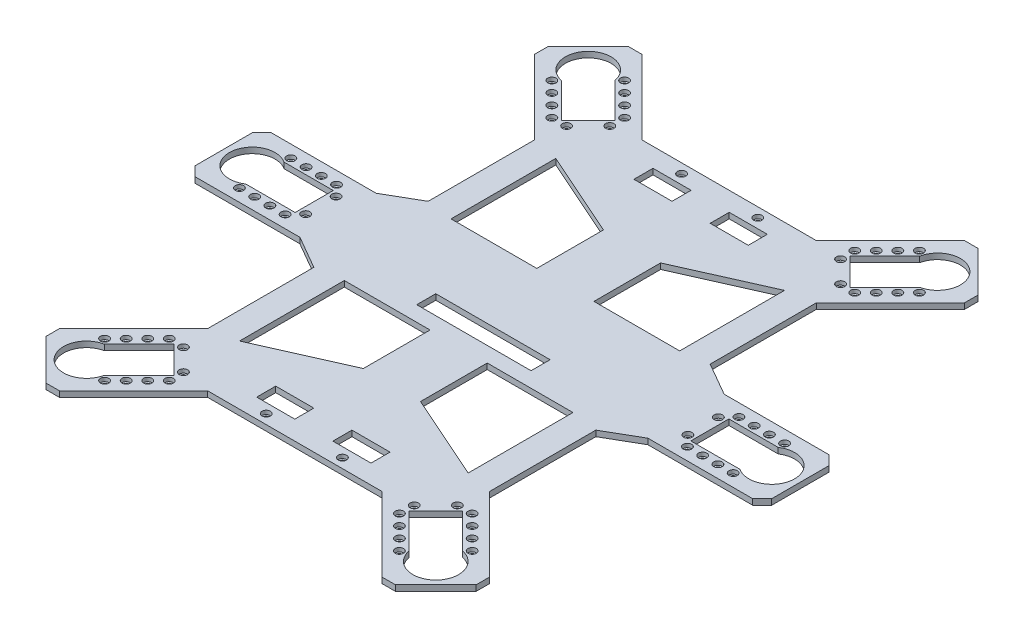
SolidWorks part; units mm, degrees
ref_plane "Front" through (0, 0, 0) normal (0, 0, 1) x (1, 0, 0)
ref_plane "Top" through (0, 0, 0) normal (0, 1, 0) x (1, 0, 0)
ref_plane "Right" through (0, 0, 0) normal (1, 0, 0) x (0, 0, -1)
sketch "草图1" plane through (0, 0, 0) normal (0, 1, 0) x (1, 0, 0)
  line L0 (-45.7157, 114) -> (45.7157, 114)
  line L1 (-74, 0) -> (74, 0) construction
  line L2 (74, -30) -> (91.3205, -20)
  line L3 (91.3205, -20) -> (146.3205, -20)
  line L4 (151.3205, -15) -> (151.3205, 15)
  line L5 (-60, 100) -> (60, -100) construction
  line L6 (-60, -100) -> (60, 100) construction
  line L7 (74, -30) -> (74, -85.7157)
  line L8 (-45.7157, -114) -> (45.7157, -114)
  line L9 (-74, 85.7157) -> (-74, 30)
  line L10 (146.3205, 20) -> (91.3205, 20)
  line L11 (74, 30) -> (91.3205, 20)
  line L12 (0, 100) -> (0, -100) construction
  line L13 (-74, 30) -> (-91.3205, 20)
  line L14 (-146.3205, 20) -> (-91.3205, 20)
  line L15 (-151.3205, -15) -> (-151.3205, 15)
  line L16 (-91.3205, -20) -> (-146.3205, -20)
  line L17 (-74, -30) -> (-91.3205, -20)
  line L18 (-74, -30) -> (-74, -85.7157)
  line L19 (74, 85.7157) -> (74, 30)
  line L20 (91.6777, 152.8909) -> (112.8909, 131.6777)
  line L21 (74, 85.7157) -> (112.8909, 124.6066)
  line L22 (45.7157, 114) -> (84.6066, 152.8909)
  line L23 (-74, 85.7157) -> (-112.8909, 124.6066)
  line L24 (-91.6777, 152.8909) -> (-112.8909, 131.6777)
  line L25 (-45.7157, 114) -> (-84.6066, 152.8909)
  line L26 (74, -85.7157) -> (112.8909, -124.6066)
  line L27 (91.6777, -152.8909) -> (112.8909, -131.6777)
  line L28 (45.7157, -114) -> (84.6066, -152.8909)
  line L29 (-74, -85.7157) -> (-112.8909, -124.6066)
  line L30 (-91.6777, -152.8909) -> (-112.8909, -131.6777)
  line L31 (-45.7157, -114) -> (-84.6066, -152.8909)
  line L32 (-84.6066, 152.8909) -> (-91.6777, 152.8909)
  line L33 (-112.8909, 131.6777) -> (-112.8909, 124.6066)
  line L34 (-151.3205, 15) -> (-146.3205, 20)
  line L35 (-146.3205, -20) -> (-151.3205, -15)
  line L36 (-112.8909, -124.6066) -> (-112.8909, -131.6777)
  line L37 (-84.6066, -152.8909) -> (-91.6777, -152.8909)
  line L38 (84.6066, -152.8909) -> (91.6777, -152.8909)
  line L39 (112.8909, -131.6777) -> (112.8909, -124.6066)
  line L40 (146.3205, -20) -> (151.3205, -15)
  line L41 (151.3205, 15) -> (146.3205, 20)
  line L42 (112.8909, 124.6066) -> (112.8909, 131.6777)
  line L43 (84.6066, 152.8909) -> (91.6777, 152.8909)
  point P0 (0, 0)
  point P12 (74, 30)
  point P16 (74, -30)
extrude "凸台-拉伸1" add sketch "草图1" along normal blind 3
sketch "草图2" plane through (0, 3, 0) normal (0, 1, 0) x (1, 0, 0)
  line L0 (151.3205, 0) -> (87.3942, 0) construction
  line L1 (151.3205, -15) -> (151.3205, 15) construction
  line L2 (103.8205, -10) -> (103.8205, 10)
  line L3 (103.8205, 10) -> (129.6873, 10)
  line L4 (103.8205, -10) -> (129.6873, -10)
  arc A0 (129.6873, -10) -> (129.6873, 10) centre (136.3205, 0) ccw
  point P11 (103.8205, 0)
  dimension "D2" = 24
  dimension "D1" = 15
  dimension "D3" = 20
  dimension "D4" = 32.5
extrude "切除-拉伸1" cut sketch "草图2" against normal up to next
sketch "草图3" plane through (0, 3, 0) normal (0, 1, 0) x (1, 0, 0)
  line L0 (129.6873, 10) -> (103.8205, 10) construction
  line L1 (103.8205, 10) -> (103.8205, -10) construction
  line L2 (151.3205, 0) -> (86.0016, 0) construction
  line L3 (151.3205, -15) -> (151.3205, 15) construction
  point P0 (105.5705, 13.5)
  point P10 (100.3205, 8)
  point P12 (113.5705, 13.5)
  point P13 (121.5705, 13.5)
  point P14 (129.5705, 13.5)
  point P15 (129.5705, -13.5)
  point P16 (121.5705, -13.5)
  point P17 (113.5705, -13.5)
  point P18 (105.5705, -13.5)
  point P19 (100.3205, -8)
  dimension "D1" = 3.5
  dimension "D2" = 1.75
  dimension "D4" = 3.5
  dimension "D5" = 2
  dimension "D3" = 4
hole_wizard "M2 凹头盖螺钉的柱形沉头孔2" positions "3D草图1" profile "草图9" counterbore size "M2" standard "ANSI Metric" end condition through all
sketch3d "3D草图1"
  point P0 (100.3205, 3, -8)
  point P3 (105.5705, 3, -13.5)
  point P6 (113.5705, 3, -13.5)
  point P9 (121.5705, 3, -13.5)
  point P12 (129.5705, 3, -13.5)
  point P15 (100.3205, 3, 8)
  point P18 (105.5705, 3, 13.5)
  point P21 (113.5705, 3, 13.5)
  point P24 (121.5705, 3, 13.5)
  point P27 (129.5705, 3, 13.5)
sketch "草图9" plane through (100.3205, 3, -8) normal (1, 0, 0) x (0, 0, 1)
  line L0 (0, 0) -> (0, 3)
  line L1 (0, 3) -> (1.2, 3)
  line L3 (1.2, 3) -> (1.2, 2)
  line L4 (1.2, 2) -> (2.2, 2)
  line L5 (2.2, 2) -> (2.2, 0)
  line L7 (2.2, 0) -> (0, 0)
  line L11 (0, -6.35) -> (0, 107.95) construction
  dimension "通孔孔直径" = 2.4
  dimension "通孔孔深度" = 3
  dimension "柱形沉头孔直径" = 4.4
  dimension "柱形沉头孔深度" = 2
sketch "草图10" plane through (0, 3, 0) normal (0, 1, 0) x (1, 0, 0)
  line L0 (102.2843, 142.2843) -> (57.3662, 97.3662) construction
  line L1 (112.8909, 131.6777) -> (91.6777, 152.8909) construction
  line L2 (75.7678, 101.6256) -> (61.6256, 115.7678)
  line L3 (61.6256, 115.7678) -> (79.9162, 134.0583)
  line L4 (75.7678, 101.6256) -> (94.0583, 119.9162)
  arc A0 (94.0583, 119.9162) -> (79.9162, 134.0583) centre (91.6777, 131.6777) ccw
  point P9 (68.6967, 108.6967)
  dimension "D1" = 15
  dimension "D2" = 32.5
extrude "切除-拉伸2" cut sketch "草图10" against normal up to next
sketch "草图16" plane through (0, 3, 0) normal (0, 1, 0) x (1, 0, 0)
  line L0 (102.2843, 142.2843) -> (58.019, 98.019) construction
  line L1 (112.8909, 131.6777) -> (91.6777, 152.8909) construction
  line L2 (61.6256, 115.7678) -> (75.7678, 101.6256) construction
  line L3 (79.9162, 134.0583) -> (61.6256, 115.7678) construction
  line L4 (60.3882, 119.4801) -> (80.2149, 139.3067) construction
  point P0 (60.3882, 119.4801)
  point P1 (60.565, 111.8787)
  point P12 (66.045, 125.1369)
  point P13 (71.7019, 130.7938)
  point P14 (77.3588, 136.4506)
  point P15 (96.4506, 117.3588)
  point P16 (90.7938, 111.7019)
  point P17 (85.1369, 106.045)
  point P18 (79.4801, 100.3882)
  point P19 (71.8787, 100.565)
  dimension "D1" = 3.5
  dimension "D2" = 2
  dimension "D3" = 1.75
  dimension "D4" = 3.5
  dimension "D5" = 8
  dimension "D6" = 8
  dimension "D7" = 8
hole_wizard "M2 凹头盖螺钉的柱形沉头孔3" positions "3D草图3" profile "草图17" counterbore size "M2" standard "ANSI Metric" end condition through all
sketch3d "3D草图3"
  point P0 (60.3882, 3, -119.4801)
  point P3 (66.045, 3, -125.1369)
  point P6 (71.7019, 3, -130.7938)
  point P9 (77.3588, 3, -136.4506)
  point P12 (60.565, 3, -111.8787)
  point P15 (71.8787, 3, -100.565)
  point P18 (79.4801, 3, -100.3882)
  point P21 (85.1369, 3, -106.045)
  point P24 (90.7938, 3, -111.7019)
  point P27 (96.4506, 3, -117.3588)
sketch "草图17" plane through (60.3882, 3, -119.4801) normal (1, 0, 0) x (0, 0, 1)
  line L0 (0, 0) -> (0, 3)
  line L1 (0, 3) -> (1.2, 3)
  line L3 (1.2, 3) -> (1.2, 2)
  line L4 (1.2, 2) -> (2.2, 2)
  line L5 (2.2, 2) -> (2.2, 0)
  line L7 (2.2, 0) -> (0, 0)
  line L11 (0, -6.35) -> (0, 107.95) construction
  dimension "通孔孔直径" = 2.4
  dimension "通孔孔深度" = 3
  dimension "柱形沉头孔直径" = 4.4
  dimension "柱形沉头孔深度" = 2
mirror "镜向5" about plane through (0, 0, 0) normal (1, 0, 0) of "切除-拉伸1", "M2 凹头盖螺钉的柱形沉头孔2"
mirror "镜向6" about plane through (0, 0, 0) normal (1, 0, 0) of "切除-拉伸2", "M2 凹头盖螺钉的柱形沉头孔3"
mirror "镜向7" about plane through (0, 0, 0) normal (0, 0, 1) of "切除-拉伸2", "M2 凹头盖螺钉的柱形沉头孔3", "镜向6"
sketch "草图18" plane through (0, 3, 0) normal (0, 1, 0) x (1, 0, 0)
  line L0 (0, 114) -> (0, -114) construction
  line L1 (45.7157, 114) -> (-45.7157, 114) construction
  line L2 (-45.7157, -114) -> (45.7157, -114) construction
  line L3 (-151.3205, 0) -> (151.3205, 0) construction
  line L4 (-151.3205, 15) -> (-151.3205, -15) construction
  line L5 (-60, -28) -> (-15, -28)
  line L6 (-15, -28) -> (-15, -63)
  line L7 (-15, -63) -> (-60, -83)
  line L8 (-60, -83) -> (-60, -28)
  line L9 (30, -10) -> (-30, -10)
  line L10 (-30, -10) -> (-30, -20)
  line L11 (-30, -20) -> (30, -20)
  line L12 (10, -94) -> (30, -94)
  line L13 (-10, -94) -> (-30, -94)
  line L14 (-10, -94) -> (-10, -104)
  line L15 (-10, -104) -> (-30, -104)
  line L16 (-30, -94) -> (-30, -104)
  line L17 (-10, -94) -> (-30, -104) construction
  line L18 (-10, -104) -> (-30, -94) construction
  line L19 (10, -104) -> (30, -104)
  line L20 (10, -94) -> (10, -104)
  line L21 (30, -94) -> (30, -104)
  line L22 (15, -63) -> (60, -83)
  line L23 (60, -83) -> (60, -28)
  line L24 (30, -10) -> (30, -20)
  line L25 (15, -28) -> (15, -63)
  line L26 (60, -28) -> (15, -28)
  line L27 (-10, 104) -> (-30, 104)
  line L28 (-30, 94) -> (-30, 104)
  line L29 (-10, 94) -> (-30, 94)
  line L30 (-10, 94) -> (-10, 104)
  line L31 (30, 94) -> (30, 104)
  line L32 (10, 104) -> (30, 104)
  line L33 (10, 94) -> (10, 104)
  line L34 (10, 94) -> (30, 94)
  line L35 (15, 63) -> (60, 83)
  line L36 (60, 83) -> (60, 28)
  line L37 (60, 28) -> (15, 28)
  line L38 (15, 28) -> (15, 63)
  line L39 (-15, 28) -> (-15, 63)
  line L40 (-60, 28) -> (-15, 28)
  line L41 (-60, 83) -> (-60, 28)
  line L42 (-15, 63) -> (-60, 83)
  point P17 (-20, -99)
  point P32 (0, -20)
  point P33 (0, -10)
  dimension "D1" = 30
  dimension "D2" = 10
  dimension "D3" = 10
  dimension "D4" = 8
  dimension "D5" = 60
  dimension "D6" = 45
  dimension "D7" = 55
  dimension "D8" = 35
  dimension "D9" = 20
  dimension "D10" = 10
  dimension "D11" = 10
  dimension "D12" = 10
extrude "切除-拉伸3" cut sketch "草图18" against normal up to next
sketch "草图19" plane through (0, 3, 0) normal (0, 1, 0) x (1, 0, 0)
  line L0 (0, 114) -> (0, -114) construction
  line L1 (45.7157, 114) -> (-45.7157, 114) construction
  line L2 (-45.7157, -114) -> (45.7157, -114) construction
  line L3 (-151.3205, 0) -> (151.3205, 0) construction
  line L4 (-151.3205, 15) -> (-151.3205, -15) construction
  line L5 (-10, 94) -> (-10, 104) construction
  point P0 (-20, 109)
  point P14 (20, 109)
  point P15 (20, -109)
  point P16 (-20, -109)
  dimension "D1" = 5
  dimension "D2" = 10
hole_wizard "M2 凹头盖螺钉的柱形沉头孔4" positions "3D草图4" profile "草图20" counterbore size "M2" standard "ANSI Metric" end condition through all
sketch3d "3D草图4"
  point P0 (-20, 3, 109)
  point P3 (20, 3, 109)
  point P6 (-20, 3, -109)
  point P9 (20, 3, -109)
sketch "草图20" plane through (-20, 3, 109) normal (1, 0, 0) x (0, 0, 1)
  line L0 (0, 0) -> (0, 3)
  line L1 (0, 3) -> (1.2, 3)
  line L3 (1.2, 3) -> (1.2, 2)
  line L4 (1.2, 2) -> (2.2, 2)
  line L5 (2.2, 2) -> (2.2, 0)
  line L7 (2.2, 0) -> (0, 0)
  line L11 (0, -6.35) -> (0, 107.95) construction
  dimension "通孔孔直径" = 2.4
  dimension "通孔孔深度" = 3
  dimension "柱形沉头孔直径" = 4.4
  dimension "柱形沉头孔深度" = 2
